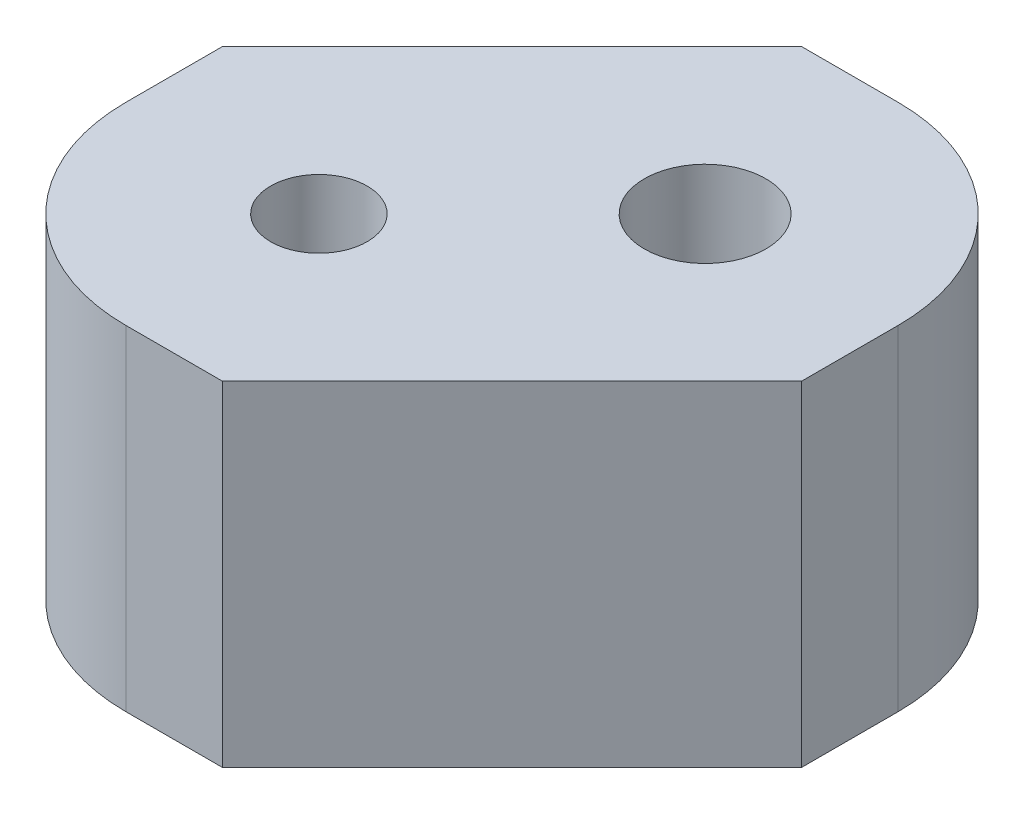
SolidWorks part; units mm, degrees
ref_plane "Front Plane" through (0, 0, 0) normal (0, 0, 1) x (1, 0, 0)
ref_plane "Top Plane" through (0, 0, 0) normal (0, 1, 0) x (1, 0, 0)
ref_plane "Right Plane" through (0, 0, 0) normal (1, 0, 0) x (0, 0, -1)
sketch "Sketch1" plane through (0, 0, 0) normal (0, 1, 0) x (1, 0, 0)
  line L1 (-9.525, -9.525) -> (9.525, -9.525)
  line L2 (-9.525, -9.525) -> (-9.525, 9.525)
  line L3 (-9.525, 9.525) -> (9.525, 9.525)
  line L4 (9.525, -9.525) -> (9.525, 9.525)
  line L5 (-9.525, -9.525) -> (9.525, 9.525) construction
  line L6 (-9.525, 9.525) -> (9.525, -9.525) construction
  point P0 (0, 0)
  dimension "D1" = 19.05
  dimension "D2" = 19.05
extrude "Boss-Extrude1" add sketch "Sketch1" along normal blind 11
sketch "Sketch2" plane through (0, 11, 0) normal (0, 1, 0) x (1, 0, 0)
  line L0 (-9.525, 9.525) -> (-9.525, -9.525) construction
  line L2 (-9.525, -9.525) -> (9.525, -9.525) construction
  line L3 (9.525, -9.525) -> (9.525, 9.525) construction
  line L4 (9.525, 9.525) -> (-9.525, 9.525) construction
  circle A0 centre (-3.175, -3.175) radius 1.5875
  circle A1 centre (3.175, 3.175) radius 1.5875
  point P8 (-1.4397, -9.525)
  dimension "D5" = 3.175
  dimension "D6" = 3.175
  dimension "D1" = 6.35
  dimension "D2" = 6.35
  dimension "D3" = 6.35
  dimension "D4" = 6.35
extrude "Cut-Extrude1" cut sketch "Sketch2" against normal through all
sketch "Sketch3" plane through (0, 11, 0) normal (0, 1, 0) x (1, 0, 0)
  circle A0 centre (3.175, 3.175) radius 2
  dimension "D1" = 4
extrude "Cut-Extrude2" cut sketch "Sketch3" against normal blind 5.7
sketch "Sketch4" plane through (0, 0, 0) normal (0, -1, 0) x (1, 0, 0)
  circle A0 centre (-3.175, 3.175) radius 2
  dimension "D1" = 4
extrude "Cut-Extrude3" cut sketch "Sketch4" against normal blind 5.7
sketch "Sketch5" plane through (0, 11, 0) normal (0, 1, 0) x (1, 0, 0)
  line L0 (-9.525, 9.525) -> (0, 9.525)
  line L1 (9.525, 9.525) -> (-9.525, 9.525) construction
  line L2 (0, 9.525) -> (-9.525, 0)
  line L3 (-9.525, 9.525) -> (-9.525, -9.525) construction
  line L4 (-9.525, 0) -> (-9.525, 9.525)
  line L5 (0, -9.525) -> (9.525, 0)
  line L6 (-9.525, -9.525) -> (9.525, -9.525) construction
  line L7 (9.525, -9.525) -> (9.525, 9.525) construction
  line L8 (9.525, 0) -> (9.525, -9.525)
  line L9 (9.525, -9.525) -> (0, -9.525)
extrude "Cut-Extrude4" cut sketch "Sketch5" against normal through all
fillet "Fillet1" radius 6.35 2 edges at (-9.525, 5.5, 9.525) (9.525, 5.5, -9.525)
